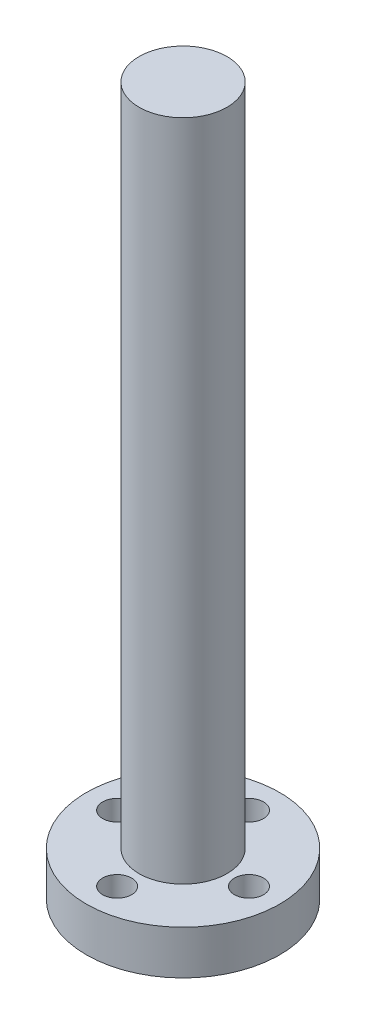
SolidWorks part; units mm, degrees
ref_plane "Front Plane" through (0, 0, 0) normal (0, 0, 1) x (1, 0, 0)
ref_plane "Top Plane" through (0, 0, 0) normal (0, 1, 0) x (1, 0, 0)
ref_plane "Right Plane" through (0, 0, 0) normal (1, 0, 0) x (0, 0, -1)
sketch "Sketch1" plane through (0, 0, 0) normal (0, 1, 0) x (1, 0, 0)
  circle A0 centre (0, 0) radius 10
extrude "Output_Shaft_20mm" add sketch "Sketch1" along normal blind 161
sketch "Sketch2" plane through (0, 0, 0) normal (0, 1, 0) x (1, 0, 0)
  circle A0 centre (0, 0) radius 22
  circle A1 centre (-15, 0) radius 3.3
  circle A2 centre (15, 0) radius 3.3
  circle A3 centre (0, -15) radius 3.3
  circle A4 centre (0, 15) radius 3.3
extrude "Output_Lower_Flange_With_Bolt_Holes" add sketch "Sketch2" along normal blind 10
equation "\"ValveDiameter\" = 50mm"
equation "\"MotorGearTeeth\" = 40"
equation "\"OutputGearTeeth\" = 80"
equation "\"GearModule\" = 1.5mm"
equation "\"PressureAngle\" = 20deg"
equation "\"GearCenterDistance\" = 90mm"
equation "\"GearWidth\" = 18mm"
equation "\"OutputShaftDiameter\" = 20mm"
equation "\"BearingOD\" = 47mm"
equation "\"BearingWidth\" = 14mm"
equation "\"PlateThickness\" = 6mm"
equation "\"ValveRotation\" = 90deg"
